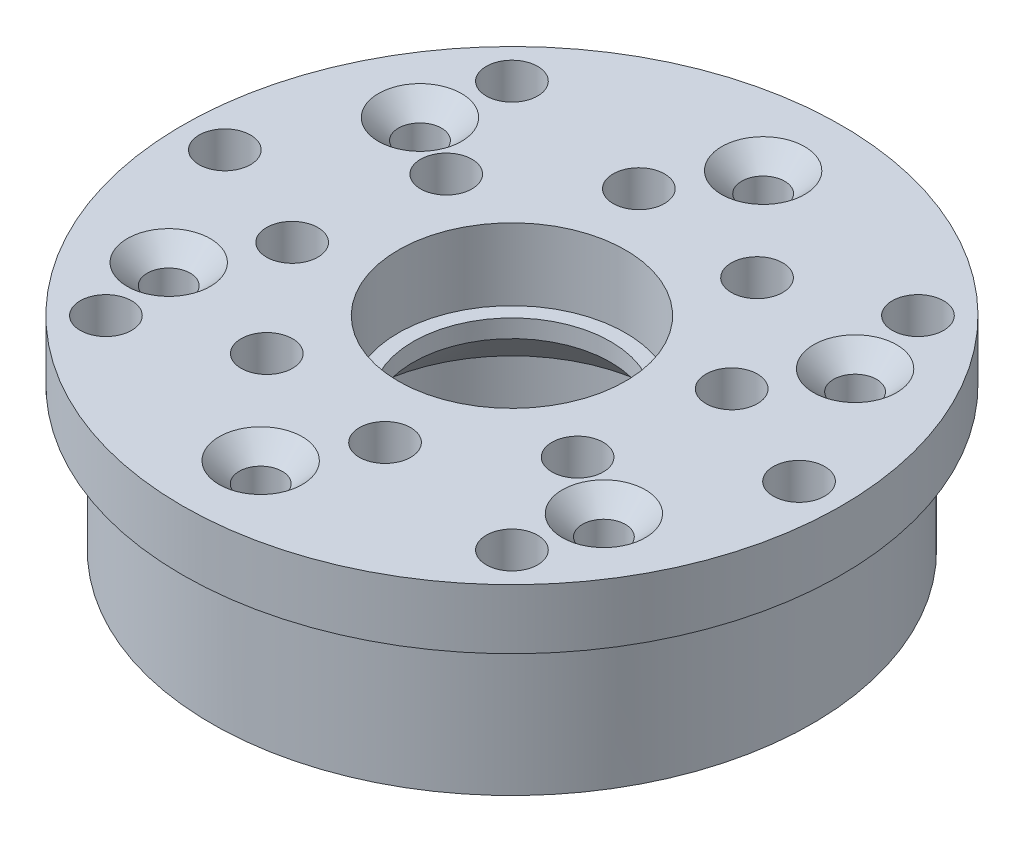
SolidWorks part; units mm, degrees
ref_plane "Front Plane" through (0, 0, 0) normal (0, 0, 1) x (1, 0, 0)
ref_plane "Top Plane" through (0, 0, 0) normal (0, 1, 0) x (1, 0, 0)
ref_plane "Right Plane" through (0, 0, 0) normal (1, 0, 0) x (0, 0, -1)
sketch "Sketch1" plane through (0, 0, 0) normal (0, 1, 0) x (1, 0, 0)
  circle A0 centre (0, 0) radius 21 construction
  circle A1 centre (0, 21) radius 2.5
  circle A2 centre (18.1865, 10.5) radius 2.5
  circle A3 centre (18.1865, -10.5) radius 2.5
  circle A4 centre (0, -21) radius 2.5
  circle A5 centre (-18.1865, -10.5) radius 2.5
  circle A6 centre (-18.1865, 10.5) radius 2.5
  circle A7 centre (0, 0) radius 25.1
  circle A8 centre (0, 0) radius 8.25
  point P18 (0, 0)
  dimension "D1" = 42
  dimension "D2" = 5
  dimension "D4" = 50.2
  dimension "D5" = 16.5
  dimension "D3" = 6
extrude "Boss-Extrude1" add sketch "Sketch1" along normal blind 10
sketch "Sketch2" plane through (0, 10, 0) normal (0, 1, 0) x (1, 0, 0)
  circle A0 centre (0, 0) radius 9.5
  circle A1 centre (0, 0) radius 15.5
  dimension "D1" = 19
  dimension "D2" = 6
extrude "Boss-Extrude2" add sketch "Sketch2" along normal blind 8.5
sketch "Sketch4" plane through (0, 10, 0) normal (0, 1, 0) x (1, 0, 0)
  circle A0 centre (0, 0) radius 9.5 construction
  circle A1 centre (0, 0) radius 8.25 construction
  circle A2 centre (0, 0) radius 9.5
  circle A3 centre (0, 0) radius 8.25
extrude "Boss-Extrude3" add sketch "Sketch4" along normal blind 2.5
sketch "Sketch3" plane through (0, 0, 0) normal (0, -1, 0) x (1, 0, 0)
  circle A0 centre (0, 0) radius 12.5
  dimension "D1" = 25
extrude "Cut-Extrude1" cut sketch "Sketch3" against normal blind 11
chamfer "Chamfer1" distance 3 angle 45 1 edges at (0, 11, -12.5)
sketch "Sketch5" plane through (0, 10, 0) normal (0, 1, 0) x (1, 0, 0)
  circle A0 centre (0, 21) radius 2.5
  circle A1 centre (18.1872, 10.4996) radius 2.5
  circle A2 centre (18.1872, -10.5011) radius 2.5
  circle A3 centre (0, -21.0014) radius 2.5
  circle A4 centre (-18.1872, -10.5011) radius 2.5
  circle A5 centre (-18.1872, 10.4996) radius 2.5
  circle A6 centre (0, 0) radius 25.1 construction
  circle A7 centre (0, 0) radius 25.1
  circle A8 centre (0, 0) radius 15.5 construction
  circle A9 centre (0, 0) radius 15.5
  circle A10 centre (0, 21) radius 2.5 construction
  point P15 (0, -0.0007)
  dimension "D2" = 6
extrude "Boss-Extrude4" add sketch "Sketch5" along normal blind 8.5
sketch "Sketch6" plane through (0, 18.5, 0) normal (0, 1, 0) x (1, 0, 0)
  circle A0 centre (0, 0) radius 25.1 construction
  circle A1 centre (0, 0) radius 25.1
  circle A2 centre (0, 0) radius 27.55
  dimension "D1" = 55.1
extrude "Boss-Extrude5" add sketch "Sketch6" against normal blind 5
sketch "Sketch8" plane through (0, 18.5, 0) normal (0, 1, 0) x (1, 0, 0)
  circle A0 centre (0, 9.5) radius 1
  circle A1 centre (0, 0) radius 9.5 construction
  circle A2 centre (0, 0) radius 9.5 construction
  dimension "D1" = 2
extrude "Cut-Extrude2" [suppressed] cut sketch "Sketch8" against normal up to surface (6 mm away)
fillet "Fillet1" [suppressed] radius 1
sketch "Sketch11" plane through (0, 18.5, 0) normal (0, 1, 0) x (1, 0, 0)
  line L0 (0, 0) -> (17.55, 30.3975) construction
  circle A0 centre (0, 0) radius 15 construction
  circle A1 centre (7.5, 12.9904) radius 2.15
  circle A2 centre (14.4889, 3.8823) radius 2.15
  circle A3 centre (12.9904, -7.5) radius 2.15
  circle A4 centre (3.8823, -14.4889) radius 2.15
  circle A5 centre (-7.5, -12.9904) radius 2.15
  circle A6 centre (-14.4889, -3.8823) radius 2.15
  circle A7 centre (0, 0) radius 24 construction
  circle A8 centre (-24, 0) radius 2.15
  circle A9 centre (-16.9706, 16.9706) radius 2.15
  circle A11 centre (16.9706, 16.9706) radius 2.15
  circle A12 centre (24, 0) radius 2.15
  circle A13 centre (16.9706, -16.9706) radius 2.15
  circle A14 centre (-12.9904, 7.5) radius 2.15
  circle A15 centre (-3.8823, 14.4889) radius 2.15
  circle A17 centre (-16.9706, -16.9706) radius 2.15
  circle A18 centre (0, -24) radius 2.15 [skipped]
  circle A19 centre (0, 24) radius 2.15 [skipped]
  point P18 (0, 0)
  point P32 (0, 0)
  dimension "D2" = 30
  dimension "D3" = 4.3
  dimension "D5" = 48
  dimension "D6" = 8
  dimension "D1" = 60
  dimension "D4" = 8
extrude "Cut-Extrude3" cut sketch "Sketch11" against normal blind 4.8
sketch "Sketch12" plane through (0, 0, 0) normal (0, -1, 0) x (1, 0, 0)
  circle A0 centre (0, 0) radius 25.1 construction
  circle A1 centre (18.1865, 10.5) radius 2.5 construction
  circle A2 centre (18.1865, -10.5) radius 2.5 construction
  circle A3 centre (0, -21) radius 2.5 construction
  circle A4 centre (-18.1865, -10.5) radius 2.5 construction
  circle A5 centre (-18.1865, 10.5) radius 2.5 construction
  circle A6 centre (0, 21) radius 2.5 construction
  circle A7 centre (0, 0) radius 12.5 construction
  circle A8 centre (0, 0) radius 25.1
  circle A9 centre (18.1865, 10.5) radius 2.5
  circle A10 centre (18.1865, -10.5) radius 2.5
  circle A11 centre (0, -21) radius 2.5
  circle A12 centre (-18.1865, -10.5) radius 2.5
  circle A13 centre (-18.1865, 10.5) radius 2.5
  circle A14 centre (0, 21) radius 2.5
  circle A15 centre (0, 0) radius 12.5
extrude "Cut-Extrude4" cut sketch "Sketch12" against normal blind 1.5
sketch "Sketch14" plane through (0, 18.5, 0) normal (0, 1, 0) x (1, 0, 0)
  circle A0 centre (0, 21) radius 2.5 construction
  circle A1 centre (0, 21) radius 2.5
  circle A2 centre (0, 21) radius 1.5
  circle A3 centre (18.1872, 10.4996) radius 1.5
  circle A4 centre (18.1872, 10.4996) radius 2.5
  circle A5 centre (18.1872, -10.5011) radius 1.5
  circle A6 centre (18.1872, -10.5011) radius 2.5
  circle A7 centre (0, -21.0014) radius 1.5
  circle A8 centre (0, -21.0014) radius 2.5
  circle A9 centre (-18.1872, -10.5011) radius 1.5
  circle A10 centre (-18.1872, -10.5011) radius 2.5
  circle A11 centre (-18.1872, 10.4996) radius 1.5
  circle A12 centre (-18.1872, 10.4996) radius 2.5
  point P22 (0, -0.0007)
  dimension "D1" = 3
extrude "Boss-Extrude8" add sketch "Sketch14" against normal blind 4.5
hole_wizard "CSK for M3 socket countersunk head screw1" positions "Sketch15" profile "Sketch16" countersink size "M3" standard "DIN" end condition through all
sketch "Sketch15" plane through (0, 18.5, 0) normal (0, 1, 0) x (1, 0, 0)
  point P0 (0, 21)
  point P3 (18.1872, 10.4996)
  point P6 (18.1872, -10.5011)
  point P9 (0, -21.0014)
  point P12 (-18.1872, -10.5011)
  point P15 (-18.1872, 10.4996)
sketch "Sketch16" plane through (0, 18.5, -21) normal (1, 0, 0) x (0, 0, 1)
  line L0 (0, 0) -> (0, 17)
  line L1 (0, 17) -> (1.8, 17)
  line L2 (1.8, 17) -> (1.8, 1.67)
  line L3 (1.8, 1.67) -> (3.47, 0)
  line L5 (3.47, 0) -> (0, 0)
  line L6 (-1.8, 1.67) -> (-3.47, 0) construction
  line L11 (0, -6.35) -> (0, 107.95) construction
  dimension "Thru Hole Dia." = 3.6
  dimension "Thru Hole Depth" = 17
  dimension "Near C'Sink Dia." = 6.94
  dimension "Near C'Sink Angle" = 90
sketch "Sketch17" plane through (0, 0, 0) normal (0, 0, 1) x (1, 0, 0)
  line L0 (-8.25, 11) -> (-12.5, 6.75)
  line L1 (-9.5, 11) -> (9.5, 11) construction
  line L2 (-8.25, 11) -> (8.25, 11) construction
  line L3 (-9.5, 11) -> (-12.5, 8)
  line L4 (-12.5, 8) -> (12.5, 8) construction
  line L6 (0, 0) -> (0, 21.2819) construction
  line L7 (-9.5, 11) -> (-8.25, 11)
  line L9 (-12.5, 8) -> (-12.5, 6.75)
revolve "Revolve1" add sketch "Sketch17" angle 360 about L6
